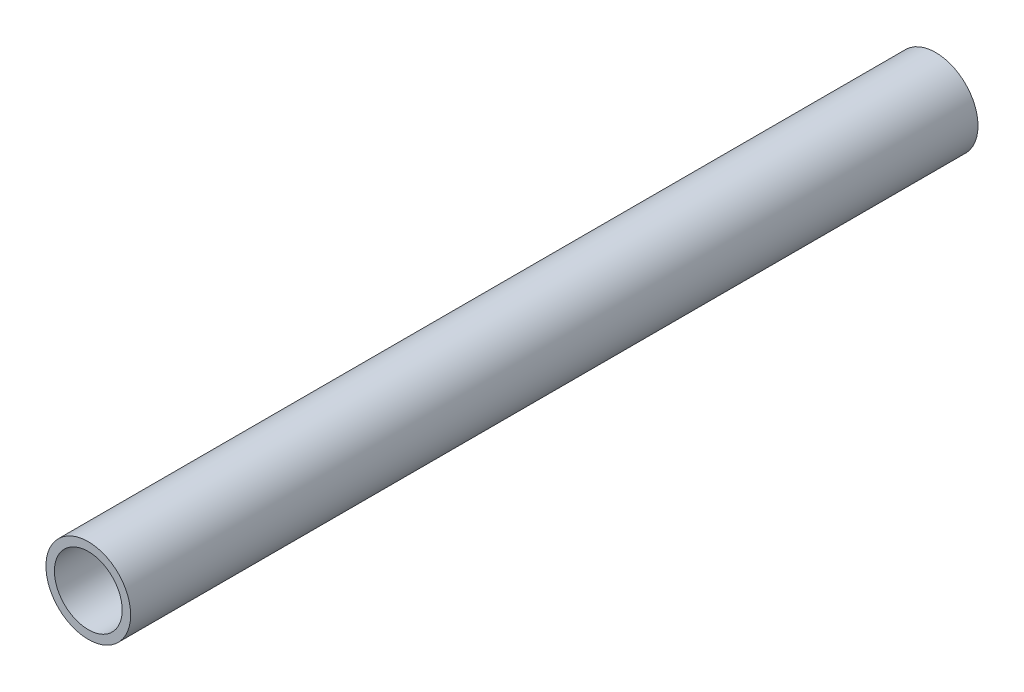
SolidWorks part; units mm, degrees
material "PVC Rigid"
ref_plane "Front Plane" through (0, 0, 0) normal (0, 0, 1) x (1, 0, 0)
ref_plane "Top Plane" through (0, 0, 0) normal (0, 1, 0) x (1, 0, 0)
ref_plane "Right Plane" through (0, 0, 0) normal (1, 0, 0) x (0, 0, -1)
sketch "Sketch1" plane through (0, 0, 0) normal (0, 0, 1) x (1, 0, 0)
  circle A0 centre (0, 0) radius 25
  circle A1 centre (0, 0) radius 20
  dimension "D1" = 50
  dimension "D2" = 5
extrude "Boss-Extrude1" add sketch "Sketch1" along normal blind 500
